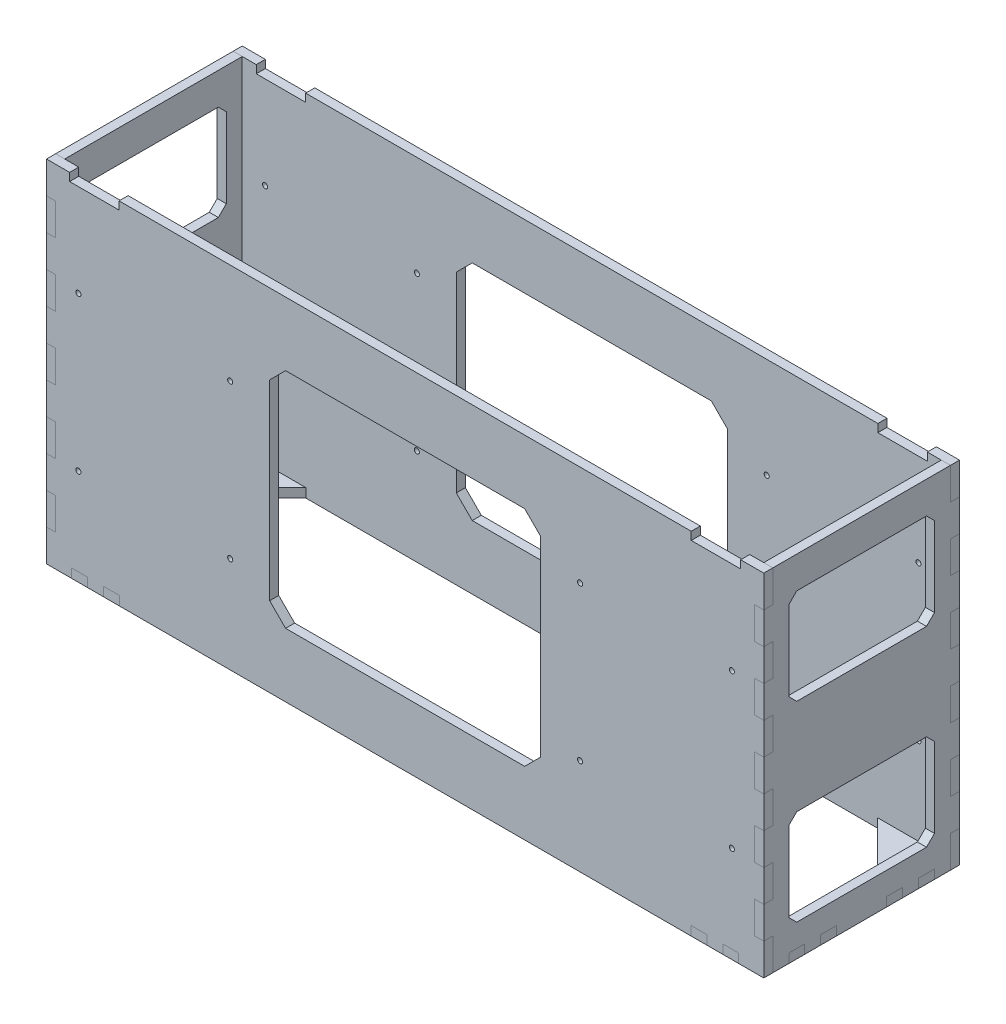
SolidWorks part; units mm, degrees
ref_plane "Front Plane" through (0, 0, 0) normal (0, 0, 1) x (1, 0, 0)
ref_plane "Top Plane" through (0, 0, 0) normal (0, 1, 0) x (1, 0, 0)
ref_plane "Right Plane" through (0, 0, 0) normal (1, 0, 0) x (0, 0, -1)
sketch "Sketch1" plane through (0, 0, 0) normal (0, 0, 1) x (1, 0, 0)
  line L0 (225, 220) -> (225, 0) construction
  line L1 (0, 0) -> (450, 0)
  line L2 (0, 0) -> (0, 220)
  line L3 (0, 220) -> (450, 220)
  line L4 (450, 0) -> (450, 220)
  circle A0 centre (20, 157) radius 1.6
  circle A1 centre (115.25, 157) radius 1.6
  circle A2 centre (115.25, 60.48) radius 1.6
  circle A3 centre (20, 60.48) radius 1.6
  circle A4 centre (430, 60.48) radius 1.6
  circle A5 centre (334.75, 60.48) radius 1.6
  circle A6 centre (334.75, 157) radius 1.6
  circle A7 centre (430, 157) radius 1.6
  dimension "D3" = 3.2
  dimension "D4" = 20
  dimension "D7" = 63
  dimension "D1" = 450
  dimension "D2" = 220
  dimension "D5" = 2
  dimension "D6" = 2
extrude "Boss-Extrude1" add sketch "Sketch1" along normal blind 5.7
sketch "Sketch8" plane through (0, 0, 0) normal (0, 0, -1) x (-1, 0, 0)
  line L0 (-450, 220) -> (0, 220) construction
  line L1 (-300, 180) -> (-150, 180)
  line L2 (-310, 170) -> (-310, 50)
  line L3 (-300, 40) -> (-150, 40)
  line L4 (-140, 170) -> (-140, 50)
  line L5 (0, 0) -> (-450, 0) construction
  line L6 (0, 220) -> (0, 0) construction
  line L7 (-450, 0) -> (-450, 220) construction
  line L8 (-310, 170) -> (-300, 180)
  line L9 (-150, 180) -> (-140, 170)
  line L10 (-140, 50) -> (-150, 40)
  line L11 (-310, 50) -> (-300, 40)
  point P0 (-310, 180)
  point P1 (-140, 40)
  point P2 (-310, 40)
  point P3 (-140, 180)
  point P8 (0, 110)
  dimension "D1" = 40
  dimension "D2" = 40
  dimension "D3" = 140
  dimension "D4" = 140
extrude "Cut-Extrude4" cut sketch "Sketch8" against normal blind 5.7
ref_plane "Plane1" through (0, 0, 61.4) normal (0, 0, 1) x (1, 0, 0)
sketch "Sketch2" plane through (0, 0, 5.7) normal (0, 0, 1) x (1, 0, 0)
  line L1 (450, 220) -> (0, 220) construction
  line L5 (0, 220) -> (0, 0) construction
  line L6 (0, 200) -> (5.7, 200)
  line L7 (0, 200) -> (0, 180)
  line L8 (0, 180) -> (5.7, 180)
  line L9 (5.7, 200) -> (5.7, 180)
  dimension "D1" = 20
  dimension "D2" = 20
  dimension "D3" = 5.7
extrude "Cut-Extrude1" cut sketch "Sketch2" against normal blind 5.7
pattern_linear "LPattern1" count 5 spacing 40 along (0, -1, 0) of "Cut-Extrude1"
ref_plane "Plane2" through (225, 0, 0) normal (-1, 0, 0) x (0, 0, 1)
mirror "Mirror5" about plane through (225, 0, 0) normal (-1, 0, 0) of "LPattern1", "Cut-Extrude1"
mirror "Mirror2" about plane through (0, 0, 61.4) normal (0, 0, 1) of bodies 113 103
sketch "Sketch4" plane through (0, 0, 0) normal (-1, 0, 0) x (0, 0, 1)
  line L1 (0, 220) -> (122.8, 220)
  line L2 (0, 220) -> (0, 0)
  line L3 (0, 0) -> (122.8, 0)
  line L4 (122.8, 220) -> (122.8, 0)
extrude "Boss-Extrude2" add sketch "Sketch4" against normal blind 5.7 separate body
sketch "Sketch6" plane through (0, 0, 0) normal (-1, 0, 0) x (0, 0, 1)
  line L1 (0, 220) -> (5.7, 220)
  line L2 (0, 220) -> (0, 200)
  line L3 (0, 200) -> (5.7, 200)
  line L4 (5.7, 220) -> (5.7, 200)
extrude "Cut-Extrude2" cut sketch "Sketch6" against normal blind 5.7
pattern_linear "LPattern2" count 6 spacing 40 along (0, -1, 0) of "Cut-Extrude2"
mirror "Mirror3" about plane through (0, 0, 61.4) normal (0, 0, 1) of "LPattern2", "Cut-Extrude2"
ref_plane "Plane3" through (0, 110, 0) normal (0, 1, 0) x (1, 0, 0)
sketch "Sketch7" plane through (0, 0, 0) normal (-1, 0, 0) x (0, 0, 1)
  line L0 (5.7, 0) -> (117.1, 0) construction
  line L1 (20.7, 20) -> (102.1, 20)
  line L2 (15.7, 25) -> (15.7, 75)
  line L3 (20.7, 80) -> (102.1, 80)
  line L4 (107.1, 25) -> (107.1, 75)
  line L5 (117.1, 20) -> (117.1, 0) construction
  line L6 (5.7, 0) -> (5.7, 20) construction
  line L7 (15.7, 75) -> (20.7, 80)
  line L8 (20.7, 20) -> (15.7, 25)
  line L9 (102.1, 20) -> (107.1, 25)
  line L10 (107.1, 75) -> (102.1, 80)
  point P0 (15.7, 20)
  point P1 (107.1, 80)
  point P2 (15.7, 80)
  point P3 (107.1, 20)
  dimension "D1" = 60
  dimension "D2" = 20
  dimension "D3" = 10
  dimension "D4" = 10
extrude "Cut-Extrude3" cut sketch "Sketch7" against normal blind 5.7
mirror "Mirror4" about plane through (0, 110, 0) normal (0, 1, 0) of "Cut-Extrude3"
sketch "Sketch9" plane through (0, 0, 0) normal (0, 0, -1) x (-1, 0, 0)
  line L0 (-450, 220) -> (0, 220) construction
  line L1 (-14.5, 220) -> (-45.5, 220)
  line L2 (-14.5, 220) -> (-14.5, 215)
  line L3 (-14.5, 215) -> (-45.5, 215)
  line L4 (-45.5, 220) -> (-45.5, 215)
  line L5 (0, 220) -> (0, 200) construction
  dimension "D1" = 31
  dimension "D2" = 14.5
  dimension "D3" = 5
extrude "Cut-Extrude5" cut sketch "Sketch9" against normal through all
mirror "Mirror6" about plane through (225, 0, 0) normal (-1, 0, 0) of "Cut-Extrude5"
sketch "Sketch11" plane through (0, 0, 0) normal (0, -1, 0) x (1, 0, 0)
  line L0 (0, 122.8) -> (450, 122.8) construction
  line L1 (15.7, 122.8) -> (25.7, 122.8)
  line L2 (15.7, 122.8) -> (15.7, 117.1)
  line L3 (15.7, 117.1) -> (25.7, 117.1)
  line L4 (25.7, 122.8) -> (25.7, 117.1)
  line L5 (0, 5.7) -> (0, 117.1) construction
  line L6 (35.7, 122.8) -> (45.7, 122.8)
  line L7 (35.7, 122.8) -> (35.7, 117.1)
  line L8 (35.7, 117.1) -> (45.7, 117.1)
  line L9 (45.7, 122.8) -> (45.7, 117.1)
  line L10 (0, 97.1) -> (5.7, 97.1)
  line L11 (0, 97.1) -> (0, 107.1)
  line L12 (0, 107.1) -> (5.7, 107.1)
  line L13 (5.7, 97.1) -> (5.7, 107.1)
  line L15 (0, 87.1) -> (5.7, 87.1)
  line L16 (0, 87.1) -> (0, 77.1)
  line L17 (0, 77.1) -> (5.7, 77.1)
  line L18 (5.7, 87.1) -> (5.7, 77.1)
  line L20 (0, 117.1) -> (450, 117.1) construction
  line L21 (5.7, 5.7) -> (5.7, 117.1) construction
  dimension "D1" = 10
  dimension "D2" = 10
  dimension "D3" = 10
  dimension "D4" = 10
  dimension "D5" = 5.7
  dimension "D6" = 5.7
  dimension "D7" = 10
  dimension "D8" = 10
  dimension "D9" = 10
  dimension "D10" = 10
  dimension "D11" = 5.7
  dimension "D12" = 5.7
extrude "Cut-Extrude6" cut sketch "Sketch11" against normal blind 5.7
sketch "Sketch12" plane through (0, 0, 0) normal (0, -1, 0) x (1, 0, 0)
  line L0 (45.7, 117.1) -> (45.7, 122.8)
  line L1 (45.7, 122.8) -> (35.7, 122.8)
  line L2 (35.7, 122.8) -> (35.7, 117.1)
  line L3 (35.7, 117.1) -> (25.7, 117.1)
  line L4 (25.7, 117.1) -> (25.7, 122.8)
  line L5 (25.7, 122.8) -> (15.7, 122.8)
  line L6 (15.7, 122.8) -> (15.7, 117.1)
  line L7 (15.7, 117.1) -> (5.7, 117.1)
  line L8 (5.7, 117.1) -> (5.7, 107.1)
  line L9 (5.7, 107.1) -> (5.7, 117.1) construction
  line L10 (5.7, 107.1) -> (0, 107.1)
  line L11 (0, 107.1) -> (0, 97.1)
  line L12 (0, 97.1) -> (5.7, 97.1)
  line L13 (5.7, 97.1) -> (5.7, 87.1)
  line L14 (5.7, 87.1) -> (5.7, 97.1) construction
  line L15 (5.7, 87.1) -> (0, 87.1)
  line L16 (0, 87.1) -> (0, 77.1)
  line L17 (0, 77.1) -> (5.7, 77.1)
  line L18 (5.7, 77.1) -> (45.7, 117.1)
extrude "Boss-Extrude3" add sketch "Sketch12" against normal blind 5.7 separate body
mirror "Mirror10" about plane through (0, 0, 61.4) normal (0, 0, 1) of "Cut-Extrude6"
mirror "Mirror11" about plane through (225, 0, 0) normal (-1, 0, 0) of bodies 127
mirror "Mirror12" about plane through (225, 0, 0) normal (-1, 0, 0) of "Cut-Extrude6", "Mirror10"
mirror "Mirror14" about plane through (0, 0, 61.4) normal (0, 0, 1) of bodies 122 131
mirror "Mirror15" about plane through (225, 0, 0) normal (-1, 0, 0) of bodies 136 122 131
other "Save Bodies1"
